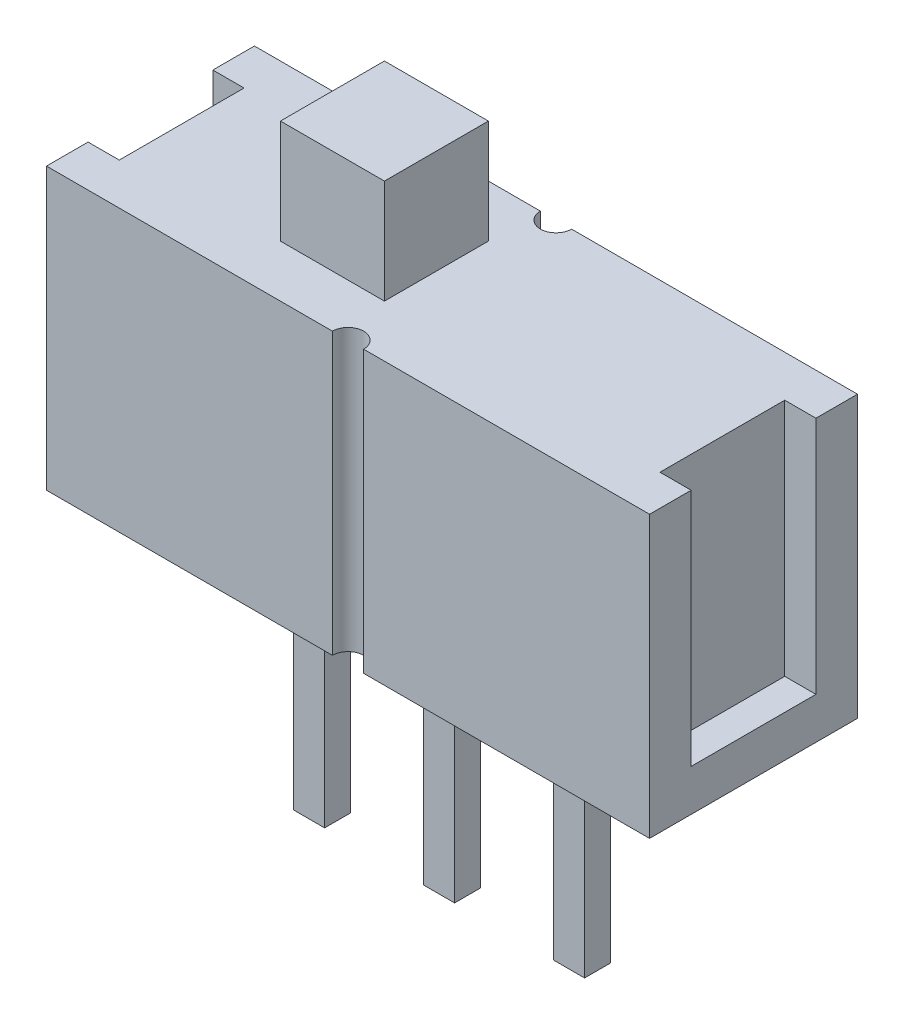
SolidWorks part; units mm, degrees
ref_plane "Front Plane" through (0, 0, 0) normal (0, 0, 1) x (1, 0, 0)
ref_plane "Top Plane" through (0, 0, 0) normal (0, 1, 0) x (1, 0, 0)
ref_plane "Right Plane" through (0, 0, 0) normal (1, 0, 0) x (0, 0, -1)
sketch "Sketch1" plane through (0, 0, 0) normal (0, 1, 0) x (1, 0, 0)
  line L0 (-5.8, -2) -> (-0.3, -2)
  line L1 (-5.8, -2) -> (-5.8, 2)
  line L2 (5.8, -2) -> (5.8, 2)
  line L3 (-5.8, 2) -> (-0.3, 2)
  line L4 (-5.8, -2) -> (5.8, 2) construction
  line L5 (5.8, -2) -> (-5.8, 2) construction
  line L6 (0.3, -2) -> (5.8, -2)
  line L7 (0.3, 2) -> (5.8, 2)
  arc A0 (0.3, -2) -> (-0.3, -2) centre (0, -2) ccw
  arc A1 (-0.3, 2) -> (0.3, 2) centre (0, 2) ccw
  point P1 (0, 0)
  dimension "D1" = 4
  dimension "D2" = 11.6
extrude "Boss-Extrude1" add sketch "Sketch1" along normal blind 5.4
sketch "Sketch3" plane through (0, 0, 0) normal (0, -1, 0) x (1, 0, 0)
  line L0 (-0.3, -0.25) -> (0.3, -0.25)
  line L1 (-0.3, -0.25) -> (-0.3, 0.25)
  line L2 (0.3, -0.25) -> (0.3, 0.25)
  line L3 (-0.3, 0.25) -> (0.3, 0.25)
  line L4 (-0.3, -0.25) -> (0.3, 0.25) construction
  line L5 (0.3, -0.25) -> (-0.3, 0.25) construction
  line L6 (2.8, -0.25) -> (2.8, 0.25)
  line L7 (2.2, 0.25) -> (2.8, 0.25)
  line L8 (2.2, -0.25) -> (2.2, 0.25)
  line L9 (2.8, -0.25) -> (2.2, 0.25) construction
  line L10 (2.2, -0.25) -> (2.8, 0.25) construction
  line L11 (2.2, -0.25) -> (2.8, -0.25)
  line L12 (-2.2, -0.25) -> (-2.2, 0.25)
  line L13 (-2.8, 0.25) -> (-2.2, 0.25)
  line L14 (-2.8, -0.25) -> (-2.8, 0.25)
  line L15 (-2.2, -0.25) -> (-2.8, 0.25) construction
  line L16 (-2.8, -0.25) -> (-2.2, 0.25) construction
  line L17 (-2.8, -0.25) -> (-2.2, -0.25)
  point P1 (0, 0)
  dimension "D1" = 0.6
  dimension "D2" = 0.5
  dimension "D3" = 2
  dimension "D4" = 2
extrude "Boss-Extrude3" add sketch "Sketch3" along normal blind 4.7
sketch "Sketch4" plane through (0, 5.4, 0) normal (0, 1, 0) x (1, 0, 0)
  line L0 (-2.3, -1) -> (-2.3, 1)
  line L1 (-2.3, -1) -> (-0.3, -1)
  line L2 (-2.3, 1) -> (-0.3, 1)
  line L3 (-0.3, -1) -> (-0.3, 1)
  line L4 (-2.3, -1) -> (-0.3, 1) construction
  line L5 (-2.3, 1) -> (-0.3, -1) construction
  point P1 (-1.3, 0)
  dimension "D1" = 2
  dimension "D2" = 2
  dimension "D3" = 0
  dimension "D4" = 0.3
extrude "Boss-Extrude4" add sketch "Sketch4" along normal blind 2
sketch "Sketch5" plane through (0, 5.4, 0) normal (0, 1, 0) x (1, 0, 0)
  line L0 (6.4, -1.2) -> (6.4, 1.2)
  line L1 (6.4, -1.2) -> (5.2, -1.2)
  line L2 (6.4, 1.2) -> (5.2, 1.2)
  line L3 (5.2, -1.2) -> (5.2, 1.2)
  line L4 (6.4, -1.2) -> (5.2, 1.2) construction
  line L5 (6.4, 1.2) -> (5.2, -1.2) construction
  line L6 (5.8, -2) -> (5.8, 2) construction
  point P1 (5.8, 0)
  dimension "D1" = 1.2
  dimension "D2" = 0.6
extrude "Cut-Extrude1" cut sketch "Sketch5" against normal blind 4.6
mirror "Mirror1" about plane through (0, 0, 0) normal (1, 0, 0) of "Cut-Extrude1"
